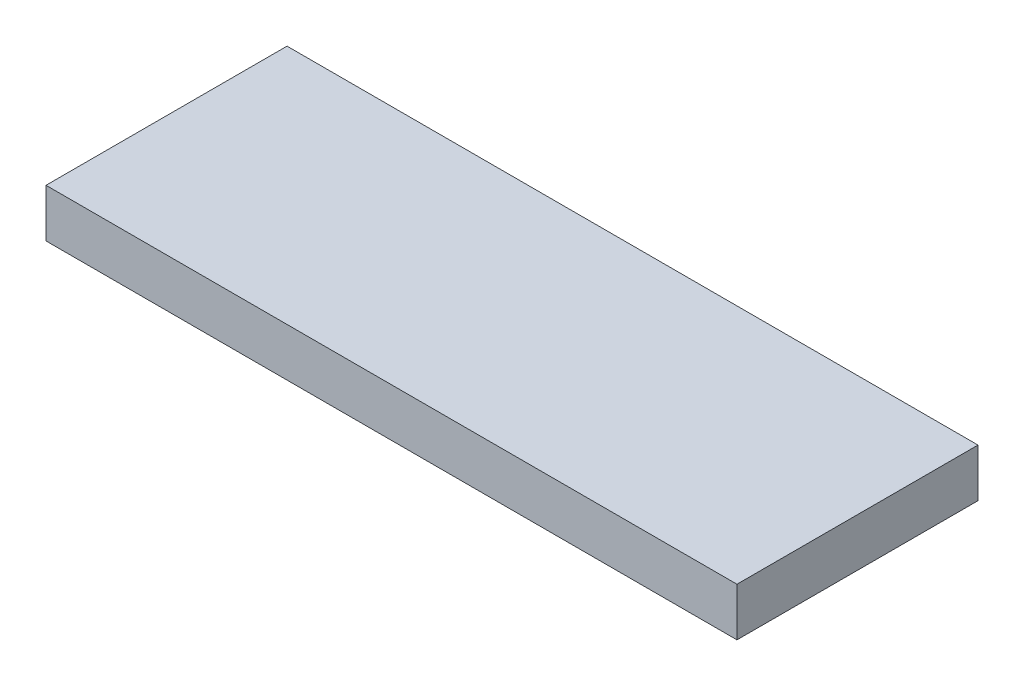
SolidWorks part; units mm, degrees
ref_plane "Plano frontal" through (0, 0, 0) normal (0, 0, 1) x (1, 0, 0)
ref_plane "Plano superior" through (0, 0, 0) normal (0, 1, 0) x (1, 0, 0)
ref_plane "Plano direito" through (0, 0, 0) normal (1, 0, 0) x (0, 0, -1)
sketch "Esboço1" plane through (0, 0, 0) normal (0, 1, 0) x (1, 0, 0)
  line L1 (-21.5, -7.5) -> (21.5, -7.5)
  line L2 (-21.5, -7.5) -> (-21.5, 7.5)
  line L3 (-21.5, 7.5) -> (21.5, 7.5)
  line L4 (21.5, -7.5) -> (21.5, 7.5)
  line L5 (-21.5, -7.5) -> (21.5, 7.5) construction
  line L6 (-21.5, 7.5) -> (21.5, -7.5) construction
  point P0 (0, 0)
  dimension "D1" = 43
  dimension "D2" = 15
extrude "Ressalto-extrusão1" add sketch "Esboço1" along normal mid plane 3
